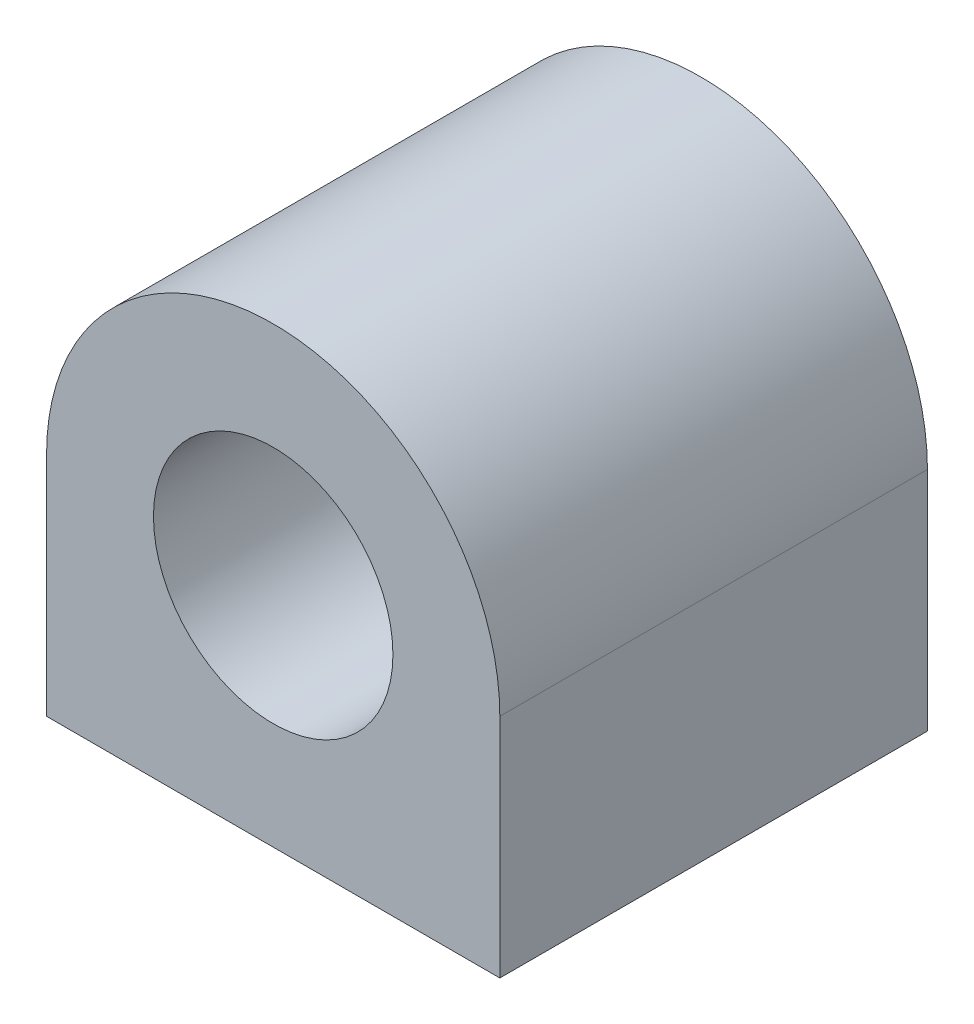
SolidWorks part; units mm, degrees
ref_plane "Front" through (0, 0, 0) normal (0, 0, 1) x (1, 0, 0)
ref_plane "Top" through (0, 0, 0) normal (0, 1, 0) x (1, 0, 0)
ref_plane "Right" through (0, 0, 0) normal (1, 0, 0) x (0, 0, -1)
sketch "Эскиз1" plane through (0, 0, 0) normal (0, 0, 1) x (1, 0, 0)
  line L0 (-10.6, 0) -> (-10.6, -10.6)
  line L1 (-10.6, -10.6) -> (10.6, -10.6)
  line L2 (10.6, -10.6) -> (10.6, 0)
  circle A0 centre (0, 0) radius 5.6
  arc A1 (10.6, 0) -> (-10.6, 0) centre (0, 0) ccw
  dimension "D1" = 11.2
  dimension "D2" = 5
extrude "Основа" add sketch "Эскиз1" along normal mid plane 20
ref_plane "Касательная плоскость" through (0, 10.6, 0) normal (0, 1, 0) x (1, 0, 0)
sketch "Эскиз3" plane through (0, -10.6, 0) normal (0, -1, 0) x (1, 0, 0)
  line L0 (0, 10) -> (0, 0) construction
  line L1 (-7.5, 0) -> (7.5, 0) construction
  line L4 (-10.6, 10) -> (10.6, 10) construction
  circle A0 centre (-7.5, 0) radius 1.2
  circle A2 centre (7.5, 0) radius 1.2
  point P5 (0, 0)
  dimension "D1" = 2.4
  dimension "D2" = 15
extrude "Крепежные отверстия" cut sketch "Эскиз3" against normal blind 11
